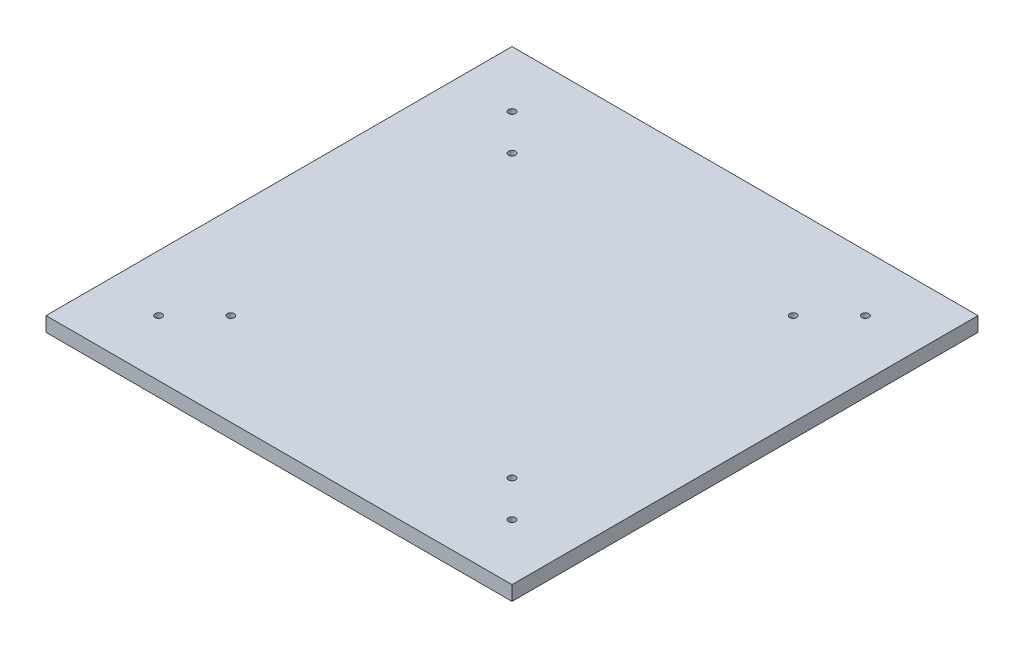
SolidWorks part; units mm, degrees
ref_plane "Front Plane" through (0, 0, 0) normal (0, 0, 1) x (1, 0, 0)
ref_plane "Top Plane" through (0, 0, 0) normal (0, 1, 0) x (1, 0, 0)
ref_plane "Right Plane" through (0, 0, 0) normal (1, 0, 0) x (0, 0, -1)
sketch "Sketch1" plane through (0, 0, 0) normal (0, 1, 0) x (1, 0, 0)
  line L0 (0, 80) -> (0, -80) construction
  line L1 (-80, -80) -> (80, -80)
  line L2 (-80, -80) -> (-80, 80)
  line L3 (-80, 80) -> (80, 80)
  line L4 (80, -80) -> (80, 80)
  line L5 (-80, -80) -> (80, 80) construction
  line L6 (-80, 80) -> (80, -80) construction
  line L7 (-80, 0) -> (80, 0) construction
  circle A0 centre (-60.6642, 60.6642) radius 1.2
  circle A1 centre (-48.2796, 48.2796) radius 1.2
  circle A2 centre (48.2796, 48.2796) radius 1.2
  circle A3 centre (60.6642, 60.6642) radius 1.2
  circle A4 centre (60.6642, -60.6642) radius 1.2
  circle A5 centre (48.2796, -48.2796) radius 1.2
  circle A6 centre (-48.2796, -48.2796) radius 1.2
  circle A7 centre (-60.6642, -60.6642) radius 1.2
  point P0 (0, 0)
  dimension "D2" = 2.4
  dimension "D3" = 2.4
  dimension "D1" = 160
extrude "Boss-Extrude1" add sketch "Sketch1" along normal blind 5
